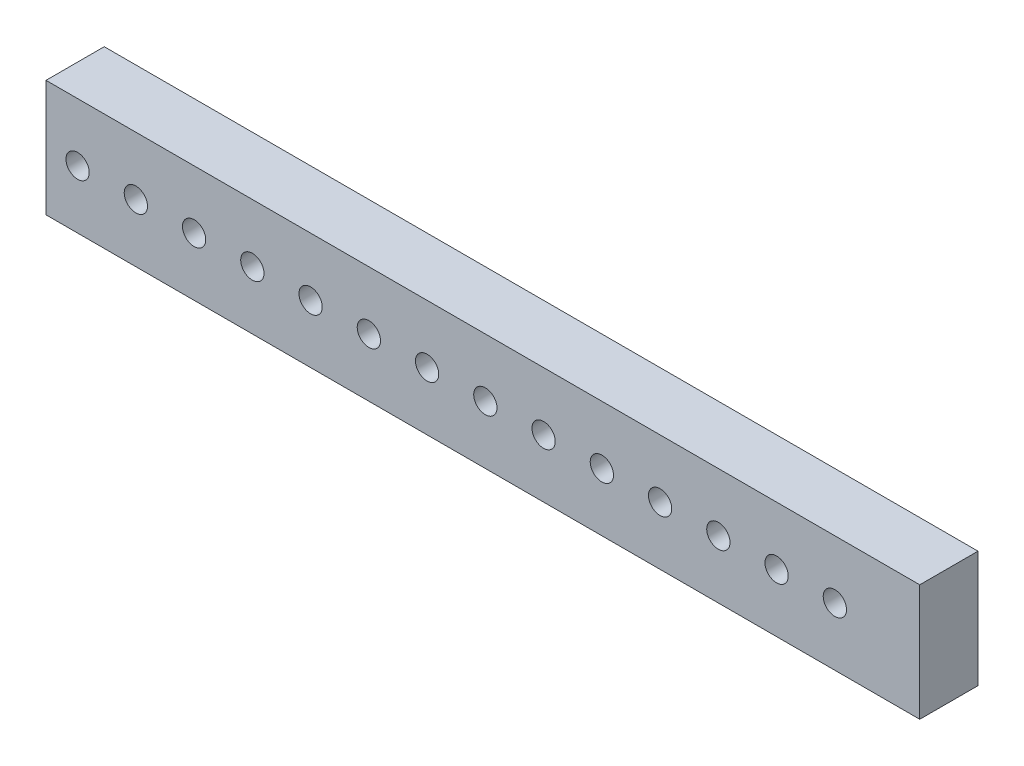
SolidWorks part; units mm, degrees
material "二氧化硅"
ref_plane "前视基准面" through (0, 0, 0) normal (0, 0, 1) x (1, 0, 0)
ref_plane "上视基准面" through (0, 0, 0) normal (0, 1, 0) x (1, 0, 0)
ref_plane "右视基准面" through (0, 0, 0) normal (1, 0, 0) x (0, 0, -1)
sketch "草图1" plane through (0, 0, 0) normal (0, 0, 1) x (1, 0, 0)
  line L1 (-75, 10) -> (75, 10)
  line L2 (-75, 10) -> (-75, -10)
  line L3 (-75, -10) -> (75, -10)
  line L4 (75, 10) -> (75, -10)
  line L5 (-75, 10) -> (75, -10) construction
  line L6 (-75, -10) -> (75, 10) construction
  point P1 (0, 0)
  dimension "D1" = 150
  dimension "D2" = 20
extrude "凸台-拉伸1" add sketch "草图1" along normal blind 10
sketch "草图2" plane through (0, 0, 0) normal (0, 0, -1) x (-1, 0, 0)
  circle A0 centre (69.574, 0) radius 2
  circle A1 centre (59.574, 0) radius 2
  circle A2 centre (49.574, 0) radius 2
  circle A3 centre (39.574, 0) radius 2
  circle A4 centre (29.574, 0) radius 2
  circle A5 centre (19.574, 0) radius 2
  circle A6 centre (9.574, 0) radius 2
  circle A7 centre (-0.426, 0) radius 2
  circle A8 centre (-10.426, 0) radius 2
  circle A9 centre (-20.426, 0) radius 2
  circle A10 centre (-30.426, 0) radius 2
  circle A11 centre (-40.426, 0) radius 2
  circle A12 centre (-50.426, 0) radius 2
  circle A13 centre (-60.426, 0) radius 2
  dimension "D1" = 14
  dimension "D2" = 4
extrude "切除-拉伸1" cut sketch "草图2" against normal blind 10
